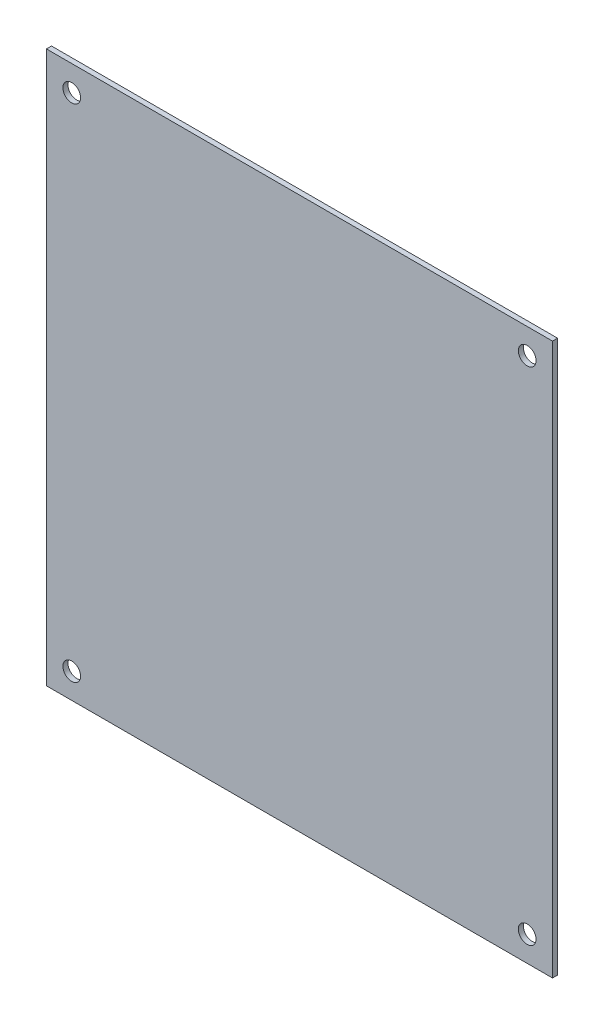
SolidWorks part; units mm, degrees
ref_plane "前视基准面" through (0, 0, 0) normal (0, 0, 1) x (1, 0, 0)
ref_plane "上视基准面" through (0, 0, 0) normal (0, 1, 0) x (1, 0, 0)
ref_plane "右视基准面" through (0, 0, 0) normal (1, 0, 0) x (0, 0, -1)
other "Configuration Table"
sketch "草图1" plane through (0, 0, 0) normal (0, 0, 1) x (1, 0, 0)
  line L1 (0, 0) -> (200, 0)
  line L2 (0, 0) -> (0, 218)
  line L3 (0, 218) -> (200, 218)
  line L4 (200, 0) -> (200, 218)
  dimension "D1" = 218
  dimension "D2" = 200
extrude "凸台-拉伸1" add sketch "草图1" along normal blind 2
sketch "草图2" plane through (0, 0, 2) normal (0, 0, 1) x (1, 0, 0)
  line L0 (100, 0) -> (100, 218) construction
  line L1 (0, 0) -> (200, 0) construction
  line L2 (200, 218) -> (0, 218) construction
  line L3 (0, 109) -> (200, 109) construction
  line L4 (0, 218) -> (0, 0) construction
  line L5 (200, 0) -> (200, 218) construction
  circle A0 centre (10, 208) radius 3.5
  circle A1 centre (190, 208) radius 3.5
  circle A2 centre (190, 10) radius 3.5
  circle A3 centre (10, 10) radius 3.5
  point P16 (2.3382, 200.5711)
  dimension "D4" = 7
  dimension "D1" = 218
  dimension "D2" = 10
  dimension "D3" = 10
extrude "切除-拉伸1" cut sketch "草图2" against normal through all
